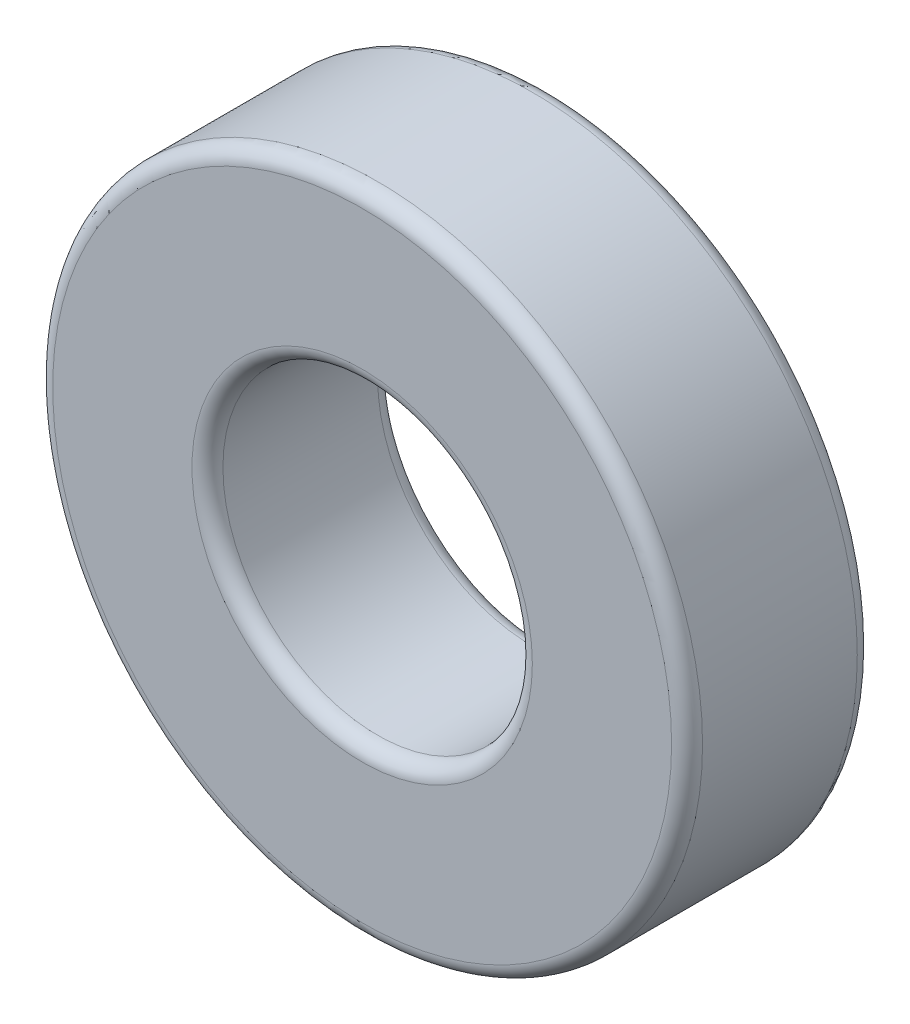
SolidWorks part; units mm, degrees
material "AISI 1020"
ref_plane "Front Plane" through (0, 0, 0) normal (0, 0, 1) x (1, 0, 0)
ref_plane "Top Plane" through (0, 0, 0) normal (0, 1, 0) x (1, 0, 0)
ref_plane "Right Plane" through (0, 0, 0) normal (1, 0, 0) x (0, 0, -1)
sketch "Bearing Dimensions" plane through (0, 0, 0) normal (0, 0, 1) x (1, 0, 0)
  circle A0 centre (0, 0) radius 10
  circle A1 centre (0, 0) radius 21
  dimension "D1" = 20
  dimension "D2" = 42
extrude "Bearing Extrude" add sketch "Bearing Dimensions" along normal mid plane 12
fillet "Fillet1" radius 1 4 edges at (10, 0, -6) (10, 0, 6) (21, 0, -6) (21, 0, 6)
